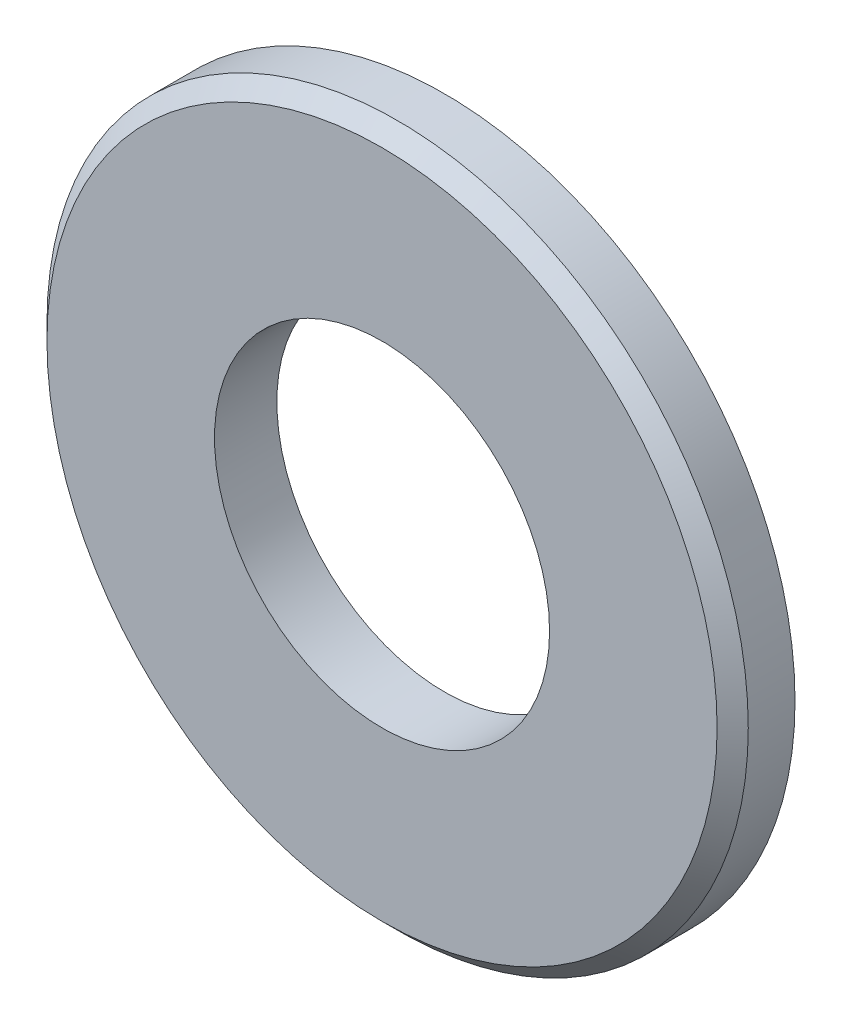
SolidWorks part; units mm, degrees
ref_plane "Front" through (0, 0, 0) normal (0, 0, 1) x (1, 0, 0)
ref_plane "Top" through (0, 0, 0) normal (0, 1, 0) x (1, 0, 0)
ref_plane "Right" through (0, 0, 0) normal (1, 0, 0) x (0, 0, -1)
sketch "Sketch1" plane through (0, 0, 0) normal (0, 0, 1) x (1, 0, 0)
  circle A0 centre (0, 0) radius 2.15
  circle A1 centre (0, 0) radius 4.5
  dimension "d1" = 4.3
  dimension "d2" = 9
extrude "Base-Extrude" add sketch "Sketch1" against normal blind 0.8
chamfer "Chamfer1" distance 0.2 angle 45 1 edges at (4.5, 0, 0)
equation "\"c@Chamfer1\"=\"h@Base-Extrude\" / 4"
